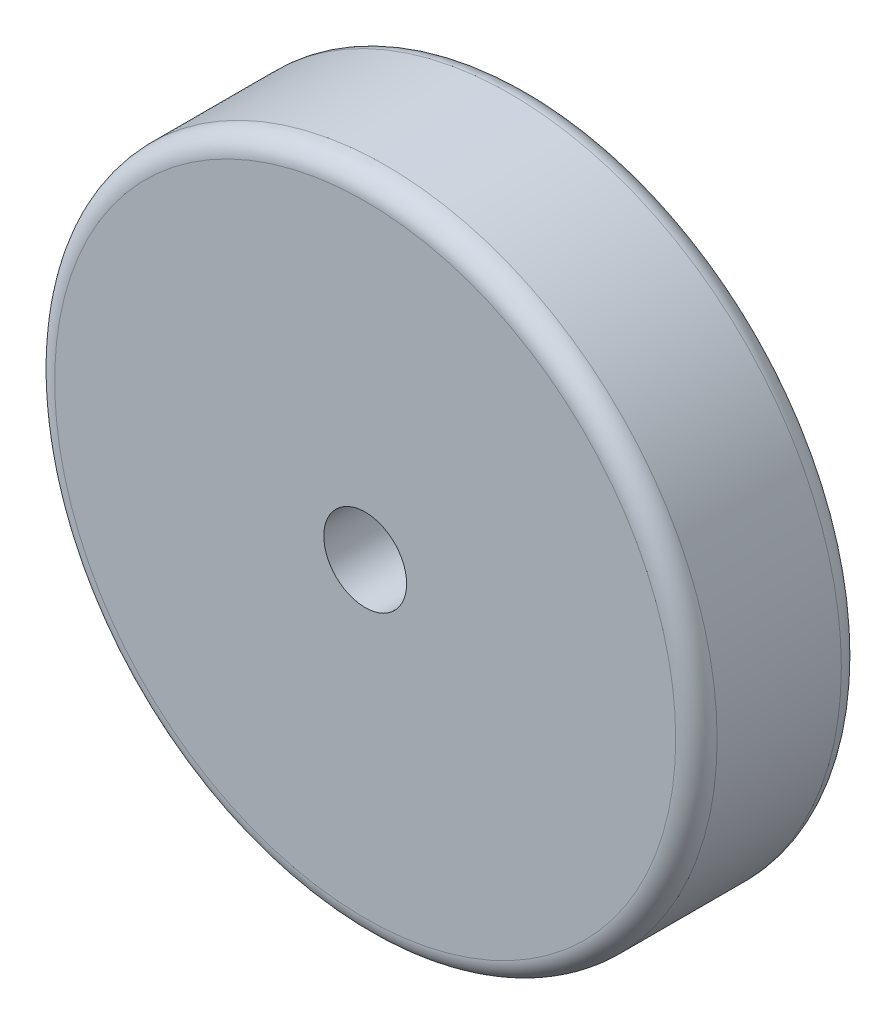
SolidWorks part; units mm, degrees
ref_plane "Front Plane" through (0, 0, 0) normal (0, 0, 1) x (1, 0, 0)
ref_plane "Top Plane" through (0, 0, 0) normal (0, 1, 0) x (1, 0, 0)
ref_plane "Right Plane" through (0, 0, 0) normal (1, 0, 0) x (0, 0, -1)
sketch "Sketch2" plane through (0, 0, 0) normal (0, 0, 1) x (1, 0, 0)
  circle A0 centre (0, 0) radius 0.5
  circle A1 centre (0, 0) radius 4
  dimension "D1" = 8
  dimension "D2" = 1
extrude "Boss-Extrude1" add sketch "Sketch2" along normal blind 2
fillet "Fillet1" radius 0.25 2 edges at (4, 0, 0) (4, 0, 2)
